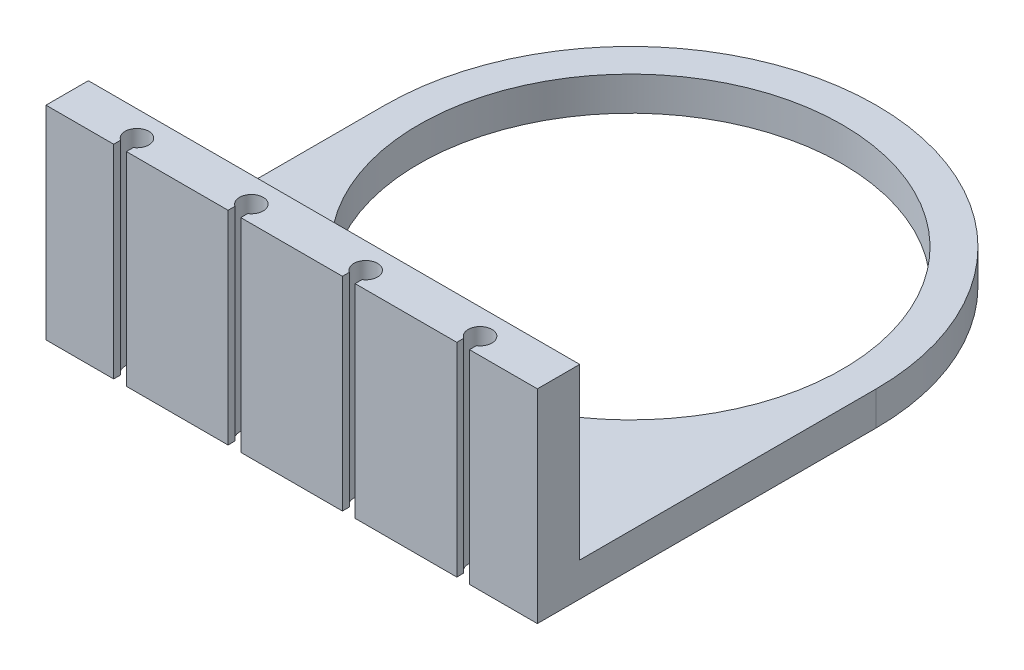
SolidWorks part; units mm, degrees
ref_plane "Front Plane" through (0, 0, 0) normal (0, 0, 1) x (1, 0, 0)
ref_plane "Top Plane" through (0, 0, 0) normal (0, 1, 0) x (1, 0, 0)
ref_plane "Right Plane" through (0, 0, 0) normal (1, 0, 0) x (0, 0, -1)
sketch "Sketch1" plane through (0, 0, 0) normal (0, 1, 0) x (1, 0, 0)
  circle A0 centre (0, 0) radius 62.5
  circle A1 centre (0, 0) radius 72.5
  dimension "D1" = 125
  dimension "D2" = 145
extrude "Boss-Extrude1" add sketch "Sketch1" along normal blind 10
sketch "Sketch2" plane through (0, 0, 0) normal (0, 0, 1) x (1, 0, 0)
  line L0 (72.5, 10) -> (-72.5, 10) construction
  line L1 (-72.5, 0) -> (-47.5, 0)
  line L2 (-72.5, 0) -> (-72.5, 10)
  line L3 (-72.5, 10) -> (-47.5, 10)
  line L4 (-47.5, 0) -> (-47.5, 10)
  line L5 (62.5, 10) -> (-62.5, 10) construction
  line L6 (72.5, 0) -> (47.5, 0)
  line L7 (72.5, 0) -> (72.5, 10)
  line L8 (72.5, 10) -> (47.5, 10)
  line L9 (47.5, 0) -> (47.5, 10)
  point P14 (-47.5, 5)
  dimension "D1" = 25
  dimension "D2" = 25
extrude "Boss-Extrude2" add sketch "Sketch2" along normal blind 100
sketch "Sketch3" plane through (0, 10, 0) normal (0, 1, 0) x (1, 0, 0)
  line L0 (72.5, -100) -> (72.5, 0) construction
  line L1 (-72.5, -100) -> (72.5, -100)
  line L2 (-72.5, -100) -> (-72.5, -50)
  line L3 (-72.5, -50) -> (72.5, -50)
  line L4 (72.5, -100) -> (72.5, -50)
extrude "Boss-Extrude3" add sketch "Sketch3" against normal up to surface (10 mm away) up to face at (0, 0, 6.77)
sketch "Sketch4" plane through (0, 10, 0) normal (0, 1, 0) x (1, 0, 0)
  circle A0 centre (0, 0) radius 62.5
extrude "Cut-Extrude1" cut sketch "Sketch4" against normal up to surface (10 mm away) up to face at (0, 0, 14.9113)
sketch "Sketch5" plane through (0, 10, 0) normal (0, 1, 0) x (1, 0, 0)
  line L0 (72.5, -100) -> (72.5, 0) construction
  line L1 (-72.5, -100) -> (72.5, -100)
  line L2 (-72.5, -100) -> (-72.5, -87.5)
  line L3 (-72.5, -87.5) -> (72.5, -87.5)
  line L4 (72.5, -100) -> (72.5, -87.5)
  dimension "D1" = 12.5
extrude "Boss-Extrude4" add sketch "Sketch5" along normal blind 50
sketch "Sketch6" plane through (0, 0, 0) normal (0, -1, 0) x (1, 0, 0)
  line L0 (-72.5, 100) -> (72.5, 100) construction
  line L1 (-72.5, 100) -> (-72.5, 0) construction
  circle A0 centre (-50.65, 95) radius 3.5
  circle A4 centre (-16.9, 95) radius 3.5
  circle A5 centre (16.85, 95) radius 3.5
  circle A6 centre (50.6, 95) radius 3.5
  point P10 (-65.6521, 90)
  point P13 (0, 0)
  dimension "D1" = 4
  dimension "D2" = 5
  dimension "D3" = 21.85
extrude "Cut-Extrude2" cut sketch "Sketch6" against normal through all both and the other way through all
sketch "Sketch7" plane through (0, 0, 0) normal (0, -1, 0) x (1, 0, 0)
  line L0 (-50.65, 95) -> (-50.65, 100) construction
  line L1 (-72.5, 100) -> (72.5, 100) construction
  line L2 (-18.775, 97.5) -> (-18.775, 102.5)
  line L3 (-52.525, 97.5) -> (-48.775, 97.5)
  line L4 (-52.525, 97.5) -> (-52.525, 102.5)
  line L5 (-52.525, 102.5) -> (-48.775, 102.5)
  line L6 (-48.775, 97.5) -> (-48.775, 102.5)
  line L7 (-52.525, 97.5) -> (-48.775, 102.5) construction
  line L8 (-52.525, 102.5) -> (-48.775, 97.5) construction
  line L9 (-18.775, 97.5) -> (-15.025, 97.5)
  line L10 (-15.025, 97.5) -> (-15.025, 102.5)
  line L11 (-18.775, 102.5) -> (-15.025, 102.5)
  line L12 (14.975, 97.5) -> (14.975, 102.5)
  line L13 (14.975, 97.5) -> (18.725, 97.5)
  line L14 (18.725, 97.5) -> (18.725, 102.5)
  line L15 (14.975, 102.5) -> (18.725, 102.5)
  line L16 (48.725, 97.5) -> (48.725, 102.5)
  line L17 (48.725, 97.5) -> (52.475, 97.5)
  line L18 (52.475, 97.5) -> (52.475, 102.5)
  line L19 (48.725, 102.5) -> (52.475, 102.5)
  dimension "D1" = 5
  dimension "D2" = 3.75
  dimension "D3" = 4
extrude "Cut-Extrude3" cut sketch "Sketch7" against normal through all both and the other way through all
